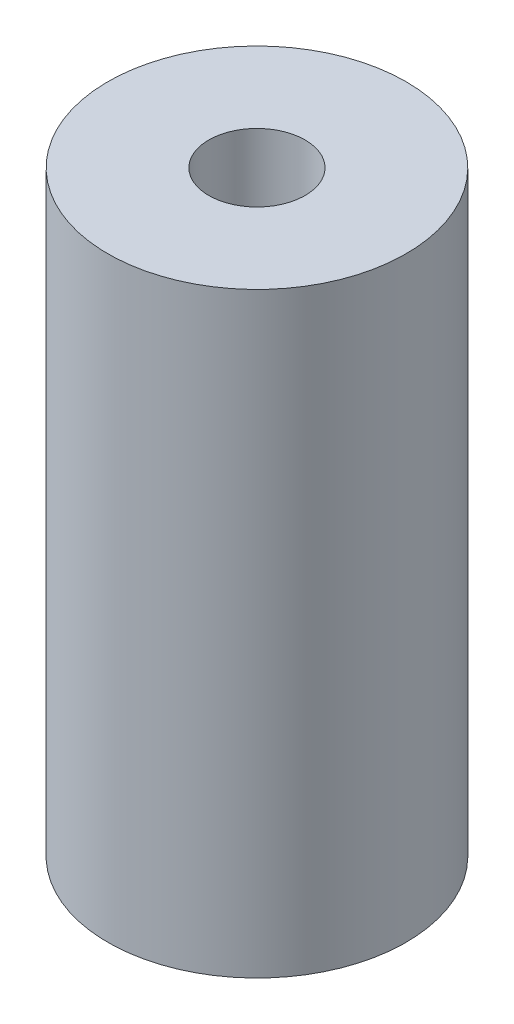
SolidWorks part; units mm, degrees
ref_plane "Front Plane" through (0, 0, 0) normal (0, 0, 1) x (1, 0, 0)
ref_plane "Top Plane" through (0, 0, 0) normal (0, 1, 0) x (1, 0, 0)
ref_plane "Right Plane" through (0, 0, 0) normal (1, 0, 0) x (0, 0, -1)
sketch "Sketch1" plane through (0, 0, 0) normal (0, 0, 1) x (1, 0, 0)
  line L0 (2.4231, 0) -> (7.5, 0)
  line L1 (7.5, 0) -> (7.5, 30)
  line L2 (7.5, 30) -> (2.4231, 30)
  line L3 (2.4231, 30) -> (2.4231, 0)
  line L4 (0, 30) -> (0, 0) construction
  dimension "D1" = 30
revolve "Revolve1" add sketch "Sketch1" angle 360 about L4
